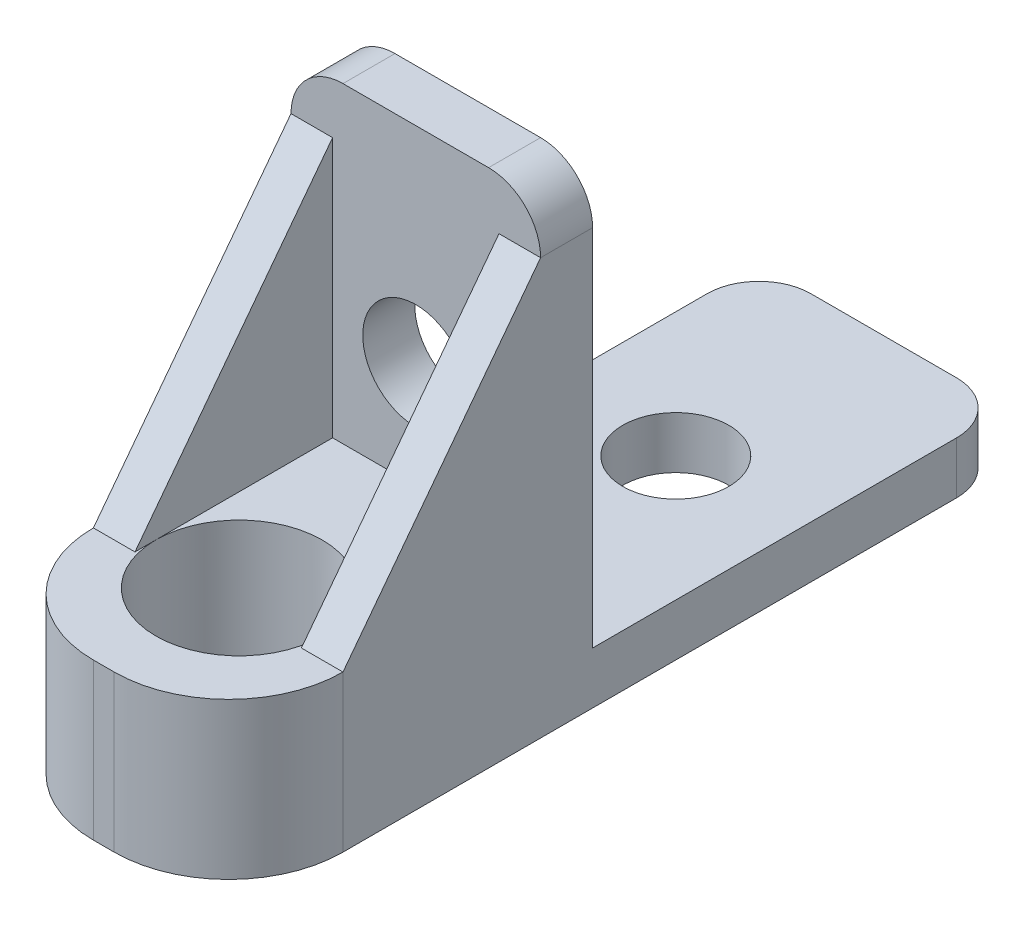
SolidWorks part; units mm, degrees
ref_plane "Спереди" through (0, 0, 0) normal (0, 0, 1) x (1, 0, 0)
ref_plane "Сверху" through (0, 0, 0) normal (0, 1, 0) x (1, 0, 0)
ref_plane "Справа" through (0, 0, 0) normal (1, 0, 0) x (0, 0, -1)
sketch "Эскиз1" plane through (0, 0, 0) normal (0, 1, 0) x (1, 0, 0)
  line L1 (2.5, 0) -> (9.5, 0)
  line L2 (0, -2.5) -> (0, -32)
  line L3 (5.5, -37.5) -> (6.5, -37.5)
  line L4 (12, -2.5) -> (12, -32)
  circle A0 centre (6, -10) radius 2.55
  circle A1 centre (6, -31) radius 4
  arc A2 (6.5, -37.5) -> (12, -32) centre (6.5, -32) ccw
  arc A3 (0, -32) -> (5.5, -37.5) centre (5.5, -32) ccw
  arc A4 (9.5, 0) -> (12, -2.5) centre (9.5, -2.5) cw
  arc A5 (0, -2.5) -> (2.5, 0) centre (2.5, -2.5) cw
  point P13 (0, -37.5)
  point P16 (12, 0)
  point P19 (0, 0)
  dimension "D3" = 5.1
  dimension "D4" = 8
  dimension "D6" = 6
  dimension "D7" = 6.5
  dimension "D8" = 5.5
  dimension "D9" = 2.5
  dimension "D1" = 12
  dimension "D2" = 37.5
  dimension "D5" = 6
  dimension "D10" = 10
extrude "Бобышка-Вытянуть1" add sketch "Эскиз1" along normal blind 2.5
sketch "Эскиз2" plane through (0, 2.5, 0) normal (0, 1, 0) x (1, 0, 0)
  line L0 (0, -2.5) -> (0, -32) construction
  line L1 (0, -20) -> (12, -20)
  line L2 (0, -20) -> (0, -22.5)
  line L3 (0, -22.5) -> (12, -22.5)
  line L4 (12, -20) -> (12, -22.5)
  line L5 (12, -32) -> (12, -2.5) construction
  line L6 (9.5, 0) -> (2.5, 0) construction
  dimension "D1" = 20
  dimension "D2" = 2.5
extrude "Бобышка-Вытянуть2" add sketch "Эскиз2" along normal blind 20
sketch "Эскиз3" plane through (0, 0, 22.5) normal (0, 0, 1) x (1, 0, 0)
  line L0 (12, 22.5) -> (12, 2.5) construction
  line L1 (0, 22.5) -> (12, 22.5) construction
  circle A0 centre (6, 12.5) radius 2.55
  dimension "D1" = 5.1
  dimension "D2" = 6
  dimension "D3" = 10
extrude "Вырез-Вытянуть1" cut sketch "Эскиз3" against normal blind 20
fillet "Скругление1" radius 2.5 2 edges at (12, 22.5, 21.25) (0, 22.5, 21.25)
sketch "Эскиз4" plane through (0, 2.5, 0) normal (0, 1, 0) x (1, 0, 0)
  line L4 (12, -22.5) -> (0, -22.5)
  line L5 (0, -22.5) -> (0, -32)
  line L6 (5.5, -37.5) -> (6.5, -37.5)
  line L7 (12, -32) -> (12, -22.5)
  line L8 (12, -22.5) -> (0, -22.5)
  line L9 (0, -22.5) -> (0, -32)
  line L10 (5.5, -37.5) -> (6.5, -37.5)
  line L11 (12, -32) -> (12, -22.5)
  arc A2 (0, -32) -> (5.5, -37.5) centre (5.5, -32) ccw
  arc A3 (6.5, -37.5) -> (12, -32) centre (6.5, -32) ccw
  arc A4 (0, -32) -> (5.5, -37.5) centre (5.5, -32) ccw
  arc A5 (6.5, -37.5) -> (12, -32) centre (6.5, -32) ccw
  dimension "D1" = 0
extrude "Бобышка-Вытянуть3" add sketch "Эскиз4" along normal blind 5
sketch "Эскиз5" plane through (12, 0, 0) normal (1, 0, 0) x (0, 0, -1)
  line L0 (-32, 7.5) -> (-22.5, 7.5)
  line L1 (-22.5, 7.5) -> (-22.5, 20)
  line L2 (-22.5, 20) -> (-32, 7.5)
extrude "Бобышка-Вытянуть4" add sketch "Эскиз5" against normal blind 2
sketch "Эскиз6" plane through (0, 0, 0) normal (-1, 0, 0) x (0, 0, 1)
  line L0 (32, 7.5) -> (22.5, 20)
  line L1 (22.5, 20) -> (22.5, 7.5)
  line L2 (22.5, 7.5) -> (32, 7.5)
extrude "Бобышка-Вытянуть5" add sketch "Эскиз6" against normal blind 2
sketch "Эскиз7" plane through (0, 2.5, 0) normal (0, -1, 0) x (1, 0, 0)
  circle A1 centre (6, 31) radius 4
  circle A2 centre (6, 31) radius 4
  dimension "D1" = 0
extrude "Вырез-Вытянуть2" cut sketch "Эскиз7" against normal through all
